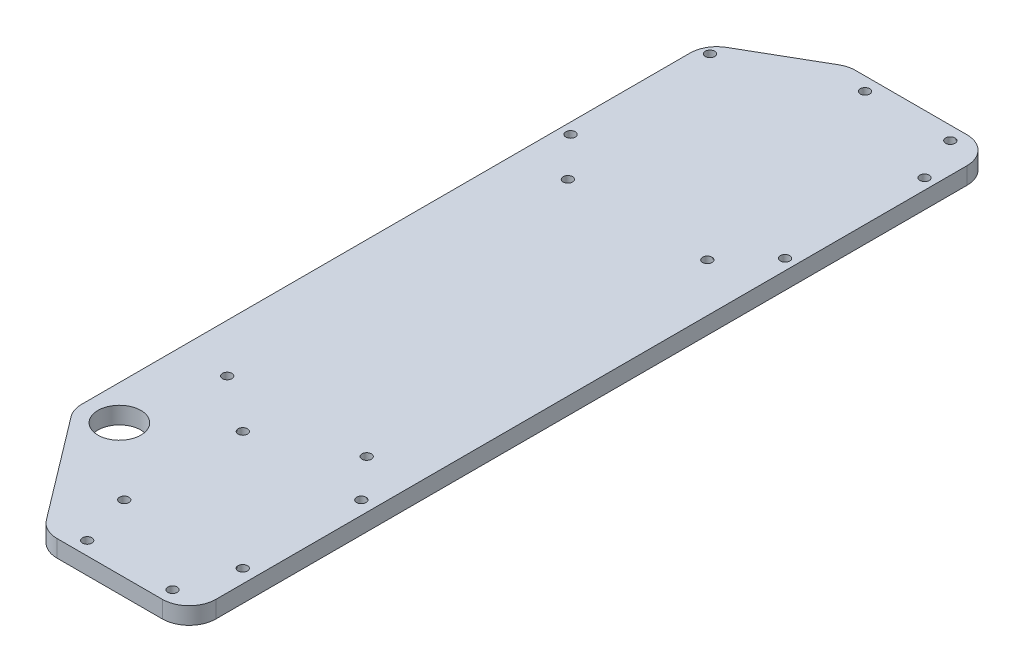
SolidWorks part; units mm, degrees
ref_plane "Front Plane" through (0, 0, 0) normal (0, 0, 1) x (1, 0, 0)
ref_plane "Top Plane" through (0, 0, 0) normal (0, 1, 0) x (1, 0, 0)
ref_plane "Right Plane" through (0, 0, 0) normal (1, 0, 0) x (0, 0, -1)
sketch "Sketch1" plane through (0, 0, 0) normal (0, 1, 0) x (1, 0, 0)
  line L0 (45, 295) -> (76.8, 295) construction
  line L1 (0, 0) -> (88, 0)
  line L2 (0, 0) -> (0, 300)
  line L3 (0, 300) -> (88, 300)
  line L4 (88, 0) -> (88, 300)
  line L5 (18, 211.2) -> (70, 211.2) construction
  line L6 (18, 211.2) -> (18, 84.2) construction
  line L7 (18, 84.2) -> (70, 84.2) construction
  line L8 (70, 211.2) -> (70, 84.2) construction
  line L9 (38.8, 69.2) -> (83, 69.2) construction
  line L10 (38.8, 69.2) -> (38.8, 25) construction
  line L11 (38.8, 25) -> (83, 25) construction
  line L12 (83, 69.2) -> (83, 25) construction
  line L13 (4, 226.2) -> (84, 226.2) construction
  line L14 (4, 226.2) -> (4, 278.2) construction
  line L15 (4, 278.2) -> (84, 278.2) construction
  line L16 (84, 226.2) -> (84, 278.2) construction
  line L17 (45, 5) -> (76.8, 5) construction
  line L18 (38.8, 25) -> (45, 5) construction
  line L19 (76.8, 5) -> (83, 25) construction
  line L20 (33.8, 0) -> (0, 44.6331)
  line L21 (33.8, 300) -> (0, 280.5109)
  line L22 (13, 49) -> (0, 49) construction
  line L23 (13, 49) -> (2.6364, 41.1518) construction
  line L24 (4, 278.2) -> (0, 278.2) construction
  line L25 (4, 278.2) -> (2.0019, 281.6652) construction
  circle A0 centre (18, 211.2) radius 1.75
  circle A1 centre (70, 84.2) radius 1.75
  circle A2 centre (18, 84.2) radius 1.75
  circle A3 centre (70, 211.2) radius 1.75
  circle A4 centre (4, 278.2) radius 1.75
  circle A5 centre (4, 226.2) radius 1.75
  circle A6 centre (84, 226.2) radius 1.75
  circle A7 centre (84, 278.2) radius 1.75
  circle A8 centre (38.8, 69.2) radius 1.75
  circle A9 centre (83, 69.2) radius 1.75
  circle A10 centre (83, 25) radius 1.75
  circle A11 centre (38.8, 25) radius 1.75
  circle A12 centre (45, 295) radius 1.75
  circle A13 centre (76.8, 295) radius 1.75
  circle A14 centre (45, 5) radius 1.75
  circle A15 centre (76.8, 5) radius 1.75
  circle A16 centre (13, 49) radius 8
  dimension "D3" = 3.5
  dimension "D14" = 3.5
  dimension "D21" = 16
  dimension "D1" = 88
  dimension "D2" = 300
  dimension "D4" = 52
  dimension "D5" = 127
  dimension "D6" = 18
  dimension "D7" = 80
  dimension "D8" = 52
  dimension "D9" = 44.2
  dimension "D11" = 4
  dimension "D12" = 15
  dimension "D13" = 15
  dimension "D10" = 5
  dimension "D15" = 5
  dimension "D16" = 11.2
  dimension "D18" = 5
  dimension "D17" = 31.8
  dimension "D19" = 11.2
  dimension "D20" = 20
  dimension "D22" = 13
  dimension "D23" = 49
  dimension "D24" = 11.2
  dimension "D25" = 11.2
extrude "Boss-Extrude1" add sketch "Sketch1" along normal blind 6.35 contours L20 L1 L4 L3 L2 A16 A15 A14 A13 A12 A11 A10 A9 A8 A7 A6 A5 A4 A3 A2 A1 A0
fillet "Fillet1" radius 10 6 edges at (88, 3.175, -300) (88, 3.175, 0) (33.8, 3.175, 0) (0, 3.175, -44.6331) (33.8, 3.175, -300) (0, 3.175, -280.5109)
equation "\"D16@Sketch1\"=\"D19@Sketch1\""
equation "\"D24@Sketch1\"=\"D19@Sketch1\""
equation "\"D13@Sketch1\"=\"D12@Sketch1\""
equation "\"D25@Sketch1\"=\"D19@Sketch1\""
